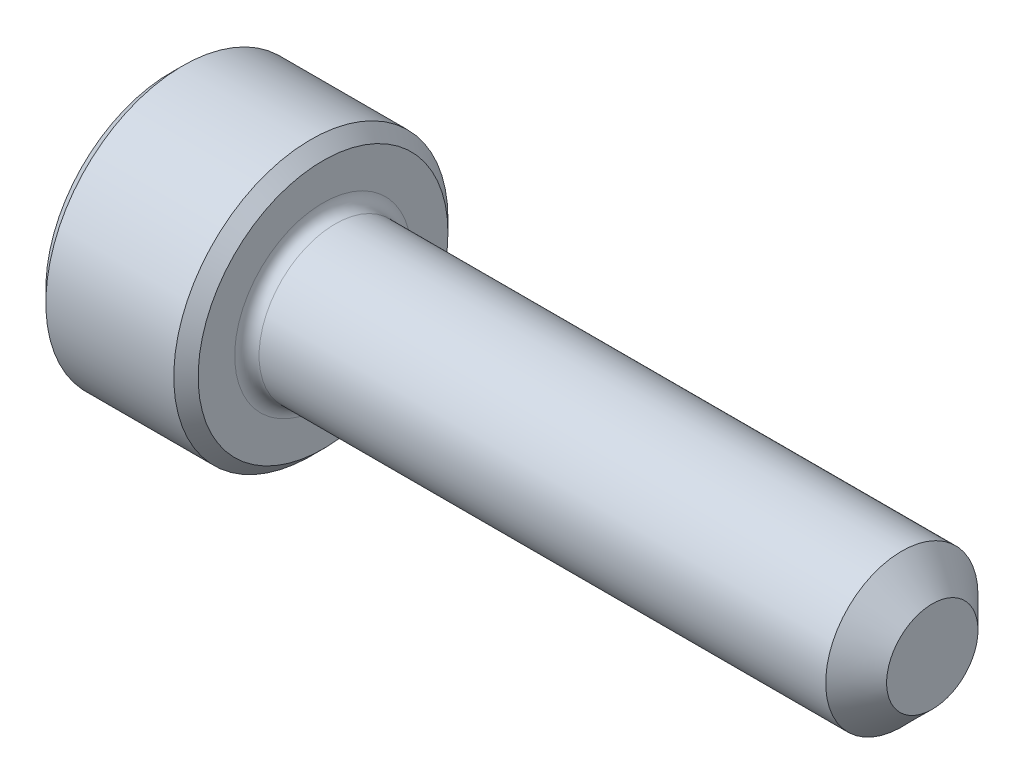
SolidWorks part; units mm, degrees
material "Литая легированная сталь"
ref_plane "Спереди" through (0, 0, 0) normal (0, 0, 1) x (1, 0, 0)
ref_plane "Сверху" through (0, 0, 0) normal (0, 1, 0) x (1, 0, 0)
ref_plane "Справа" through (0, 0, 0) normal (1, 0, 0) x (0, 0, -1)
sketch "Эскиз1" plane through (0, 0, 0) normal (0, 0, 1) x (1, 0, 0)
  line L0 (0, 0) -> (0, 2.05)
  line L1 (0.2, 2.25) -> (2.3, 2.25)
  line L2 (2.5, 2.05) -> (2.5, 1.45)
  line L3 (2.7, 1.25) -> (12, 1.25)
  line L4 (12, 1.25) -> (12.5, 0.75)
  line L5 (12.5, 0.75) -> (12.5, 0)
  line L6 (12.5, 0) -> (0, 0)
  line L7 (0, 0) -> (-1.7274, 0) construction
  line L8 (2.3, 2.25) -> (2.5, 2.05)
  line L9 (0, 2.05) -> (0.2, 2.25)
  arc A0 (2.5, 1.45) -> (2.7, 1.25) centre (2.7, 1.45) ccw
  point P1 (0, 2.25)
  point P4 (2.5, 2.25)
  point P7 (12.5, 1.25)
  dimension "D5" = 0.2
  dimension "D1" = 4.5
  dimension "D2" = 2.5
  dimension "D3" = 10
  dimension "D4" = 2.5
revolve "Повернуть1" add sketch "Эскиз1" angle 360 about L7
sketch "Эскиз2" plane through (0, 0, 0) normal (-1, 0, 0) x (0, 0, 1)
  line L1 (0, 1.1547) -> (-1, 0.5774)
  line L2 (-1, 0.5774) -> (-1, -0.5774)
  line L3 (-1, -0.5774) -> (0, -1.1547)
  line L4 (0, -1.1547) -> (1, -0.5774)
  line L5 (1, -0.5774) -> (1, 0.5774)
  line L6 (1, 0.5774) -> (0, 1.1547)
  circle A0 centre (0, 0) radius 1 construction
  dimension "D1" = 2
extrude "Вырез-Вытянуть1" cut sketch "Эскиз2" against normal blind 1.1
